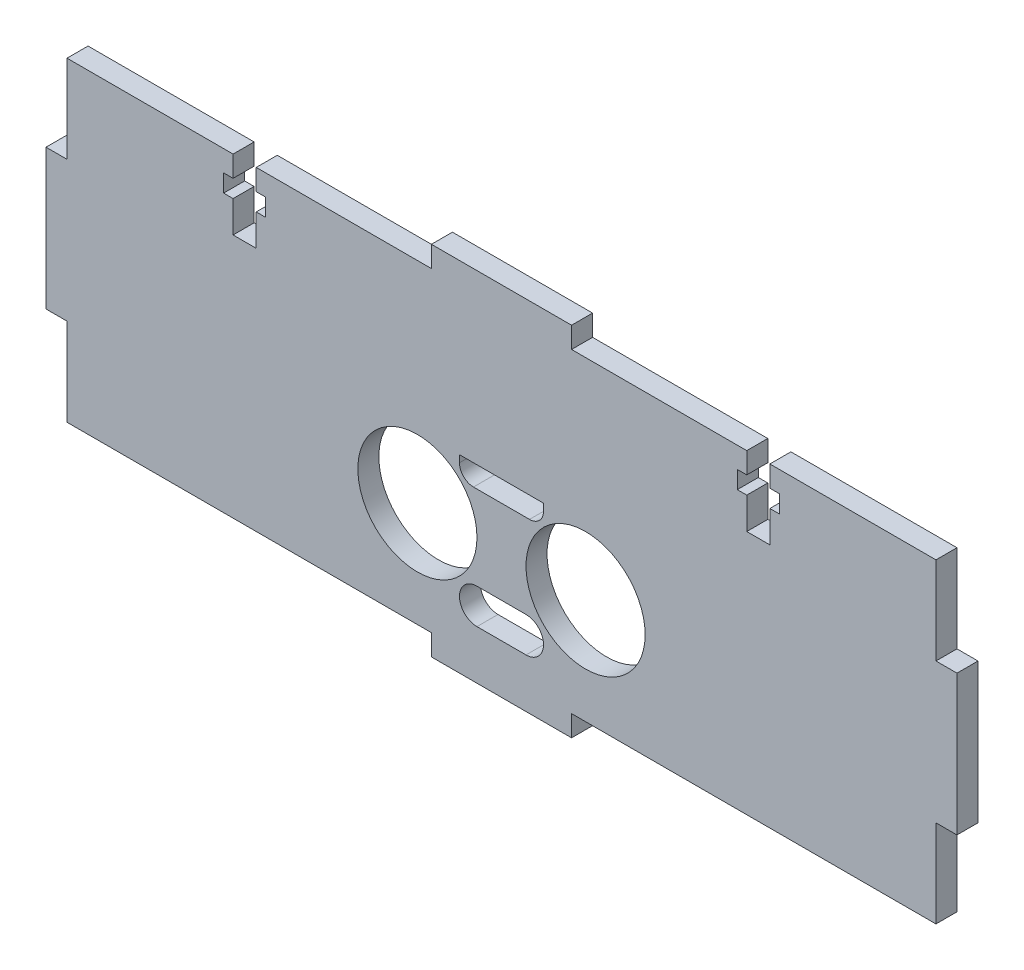
SolidWorks part; units mm, degrees
ref_plane "Front Plane" through (0, 0, 0) normal (0, 0, 1) x (1, 0, 0)
ref_plane "Top Plane" through (0, 0, 0) normal (0, 1, 0) x (1, 0, 0)
ref_plane "Right Plane" through (0, 0, 0) normal (1, 0, 0) x (0, 0, -1)
sketch "Sketch1" plane through (0, 0, 0) normal (0, 0, 1) x (1, 0, 0)
  line L0 (-3.5, -16) -> (3.5, -16) construction
  line L1 (62, -22.5) -> (-62, -22.5)
  line L2 (62, -22.5) -> (62, 22.5)
  line L3 (62, 22.5) -> (-62, 22.5)
  line L4 (-62, -22.5) -> (-62, 22.5)
  line L5 (62, -22.5) -> (-62, 22.5) construction
  line L6 (62, 22.5) -> (-62, -22.5) construction
  line L7 (-3.5, -13.5) -> (3.5, -13.5)
  line L8 (-3.5, -18.5) -> (3.5, -18.5)
  line L9 (0, -55) -> (0, 55) construction
  line L10 (4, -1.5) -> (-4, -1.5)
  line L11 (6, 0.5) -> (6, 1.5)
  line L12 (6, 1.5) -> (-6, 1.5)
  line L13 (-6, 0.5) -> (-6, 1.5)
  line L14 (6, -1.5) -> (-6, 1.5) construction
  line L15 (6, 1.5) -> (-6, -1.5) construction
  line L16 (10, -25.5) -> (-10, -25.5)
  line L17 (10, -25.5) -> (10, -22.5)
  line L18 (10, -22.5) -> (-10, -22.5)
  line L19 (-10, -25.5) -> (-10, -22.5)
  line L20 (10, -25.5) -> (-10, -22.5) construction
  line L21 (10, -22.5) -> (-10, -25.5) construction
  line L22 (-65, -10) -> (-62, -10)
  line L23 (-65, -10) -> (-65, 10)
  line L24 (-65, 10) -> (-62, 10)
  line L25 (-62, -10) -> (-62, 10)
  line L26 (-65, -10) -> (-62, 10) construction
  line L27 (-65, 10) -> (-62, -10) construction
  line L28 (65, 10) -> (62, 10)
  line L29 (62, -10) -> (62, 10)
  line L30 (65, -10) -> (62, -10)
  line L31 (65, -10) -> (65, 10)
  line L32 (55, 0) -> (-55, 0) construction
  line L33 (10, 22.5) -> (-10, 22.5)
  line L34 (-10, 25.5) -> (-10, 22.5)
  line L35 (10, 25.5) -> (-10, 25.5)
  line L36 (10, 25.5) -> (10, 22.5)
  line L37 (33.65, 17) -> (39.65, 17)
  line L38 (-35, 12.5) -> (-38.3, 12.5)
  line L39 (-35, 12.5) -> (-35, 22.5)
  line L40 (-35, 22.5) -> (-38.3, 22.5)
  line L41 (-38.3, 12.5) -> (-38.3, 22.5)
  line L42 (-35, 12.5) -> (-38.3, 22.5) construction
  line L43 (-35, 22.5) -> (-38.3, 12.5) construction
  line L44 (-33.65, 19.5) -> (-39.65, 19.5)
  line L45 (-33.65, 19.5) -> (-33.65, 17)
  line L46 (-33.65, 17) -> (-39.65, 17)
  line L47 (-39.65, 19.5) -> (-39.65, 17)
  line L48 (-33.65, 19.5) -> (-39.65, 17) construction
  line L49 (-33.65, 17) -> (-39.65, 19.5) construction
  line L50 (39.65, 19.5) -> (39.65, 17)
  line L51 (33.65, 19.5) -> (39.65, 19.5)
  line L52 (33.65, 19.5) -> (33.65, 17)
  line L53 (35, 22.5) -> (38.3, 22.5)
  line L54 (38.3, 12.5) -> (38.3, 22.5)
  line L55 (35, 12.5) -> (38.3, 12.5)
  line L56 (35, 12.5) -> (35, 22.5)
  circle A0 centre (-12, -7.5) radius 8.5
  circle A1 centre (12, -7.5) radius 8.5
  arc A2 (-3.5, -13.5) -> (-3.5, -18.5) centre (-3.5, -16) ccw
  arc A3 (3.5, -18.5) -> (3.5, -13.5) centre (3.5, -16) ccw
  arc A4 (4, -1.5) -> (6, 0.5) centre (4, 0.5) ccw
  arc A5 (-4, -1.5) -> (-6, 0.5) centre (-4, 0.5) cw
  point P0 (0, 0)
  point P10 (0, -16)
  point P17 (-36.65, 17.5)
  point P18 (-63.5, 0)
  point P19 (0, 0)
  point P31 (0, -24)
  point P55 (-36.65, 18.25)
  dimension "D3" = 17
  dimension "D8" = 2.5
  dimension "D13" = 2
  dimension "D1" = 124
  dimension "D2" = 45
  dimension "D4" = 24
  dimension "D5" = 15
  dimension "D6" = 12
  dimension "D7" = 7
  dimension "D9" = 6
  dimension "D10" = 6
  dimension "D11" = 3
  dimension "D12" = 12
  dimension "D14" = 20
  dimension "D15" = 3
  dimension "D16" = 20
  dimension "D17" = 3
  dimension "D18" = 3.3
  dimension "D19" = 10
  dimension "D20" = 6
  dimension "D21" = 2.5
  dimension "D22" = 3
  dimension "D23" = 25
extrude "Boss-Extrude1" add sketch "Sketch1" along normal blind 3 contours L24 L23 L22 L4 | L4 L1 L2 L3 A3 L8 A2 L7 A1 A0 L10 A5 L13 L12 L11 A4 | L36 L35 L34 L3 | L30 L31 L28 L2 | L19 L16 L17 L1
